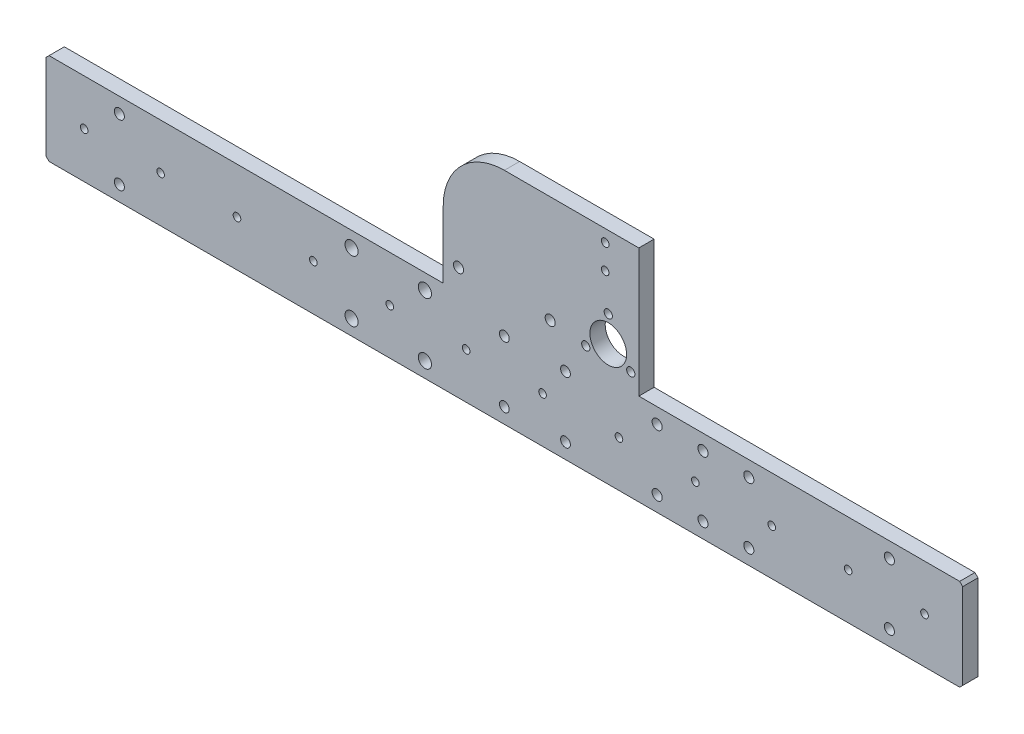
SolidWorks part; units mm, degrees
material "5052-O"
ref_plane "前基準面" through (0, 0, 0) normal (0, 0, 1) x (1, 0, 0)
ref_plane "上基準面" through (0, 0, 0) normal (0, 1, 0) x (1, 0, 0)
ref_plane "右基準面" through (0, 0, 0) normal (1, 0, 0) x (0, 0, -1)
sketch "草圖1" plane through (0, 0, 0) normal (0, 0, 1) x (1, 0, 0)
  line L1 (-150, -15) -> (150, -15)
  line L2 (-150, -15) -> (-150, 15)
  line L3 (-150, 15) -> (150, 15)
  line L4 (150, -15) -> (150, 15)
  line L5 (-150, -15) -> (150, 15) construction
  line L6 (-150, 15) -> (150, -15) construction
  point P0 (0, 0)
  dimension "D1" = 300
  dimension "D2" = 30
extrude "填料-伸長1" add sketch "草圖1" along normal blind 5
chamfer "導角1" distance 1 angle 45 4 edges at (150, -15, 2.5) (150, 15, 2.5) (-150, -15, 2.5) (-150, 15, 2.5)
hole_wizard "M3 餘隙孔1" positions "草圖7" profile "草圖8" hole size "M3" standard "Ansi Metric" end condition through all
sketch "草圖7" plane through (0, 0, 5) normal (0, 0, 1) x (1, 0, 0)
  line L0 (0, 0) -> (10, 0) construction
  line L4 (0, -10) -> (20, -10) construction
  line L5 (0, -10) -> (0, 10) construction
  line L6 (0, 10) -> (20, 10) construction
  line L7 (20, -10) -> (20, 10) construction
  line L8 (0, -10) -> (20, 10) construction
  line L9 (0, 10) -> (20, -10) construction
  point P9 (20, 10)
  point P60 (0, -10)
  point P61 (0, 10)
  point P62 (20, -10)
  dimension "D1" = 10
  dimension "D2" = 20
  dimension "D3" = 20
sketch "草圖8" plane through (20, -10, 5) normal (1, 0, 0) x (0, -1, 0)
  line L0 (0, 0) -> (0, 5)
  line L1 (0, 5) -> (1.6, 5)
  line L2 (1.6, 5) -> (1.6, 0)
  line L5 (1.6, 0) -> (0, 0)
  line L11 (0, -6.35) -> (0, 107.95) construction
  dimension "貫穿孔直徑" = 3.2
  dimension "貫穿孔深度" = 5
hole_wizard "M3x0.5 螺紋孔1" positions "草圖3" profile "草圖4" tap size "M3x0.5" standard "Ansi Metric" end condition through all
sketch "草圖3" plane through (0, 0, 5) normal (0, 0, 1) x (1, 0, 0)
  line L0 (-12.5, 0) -> (12.5, 0) construction
  point P0 (-12.5, 0)
  dimension "D1" = 25
sketch "草圖4" plane through (-12.5, 0, 5) normal (1, 0, 0) x (0, -1, 0)
  line L0 (0, 0) -> (0, 5)
  line L1 (0, 5) -> (1.25, 5)
  line L2 (1.25, 5) -> (1.25, 0)
  line L5 (1.25, 0) -> (0, 0)
  line L11 (0, -6.35) -> (0, 107.95) construction
  dimension "貫穿螺孔鑽直徑" = 2.5
  dimension "貫穿螺孔鑽深度" = 5
hole_wizard "M4x0.7 螺紋孔1" positions "草圖9" profile "草圖10" tap size "M4x0.7" standard "Ansi Metric" end condition through all
sketch "草圖9" plane through (0, 0, 5) normal (0, 0, 1) x (1, 0, 0)
  line L1 (50, -10) -> (80, -10) construction
  line L2 (50, -10) -> (50, 10) construction
  line L3 (50, 10) -> (80, 10) construction
  line L4 (80, -10) -> (80, 10) construction
  line L5 (50, -10) -> (80, 10) construction
  line L6 (50, 10) -> (80, -10) construction
  line L7 (0, 0) -> (65, 0) construction
  point P2 (80, 10)
  point P55 (50, -10)
  point P56 (50, 10)
  point P57 (80, -10)
  point P68 (65, 0)
  point P78 (65, 10)
  point P80 (65, -10)
  dimension "D1" = 30
  dimension "D2" = 20
  dimension "D3" = 65
sketch "草圖10" plane through (80, 10, 5) normal (1, 0, 0) x (0, -1, 0)
  line L0 (0, 0) -> (0, 5)
  line L1 (0, 5) -> (1.65, 5)
  line L2 (1.65, 5) -> (1.65, 0)
  line L5 (1.65, 0) -> (0, 0)
  line L11 (0, -6.35) -> (0, 107.95) construction
  dimension "砮 脸ふ苝 畖" = 3.3
  dimension "砮 脸ふ苝瞏 " = 5
hole_wizard "M4x0.7 螺紋孔2" positions "草圖11" profile "草圖12" tap size "M4x0.7" standard "Ansi Metric" end condition through all
sketch "草圖11" plane through (0, 0, 5) normal (0, 0, 1) x (1, 0, 0)
  line L0 (-150, 0) -> (-126, 0) construction
  line L1 (-150, 14) -> (-150, -14) construction
  line L4 (-126, -10) -> (-126, 10) construction
  point P9 (-126, -10)
  point P10 (-126, 10)
  dimension "D1" = 20
  dimension "D2" = 24
sketch "草圖12" plane through (-126, 10, 5) normal (1, 0, 0) x (0, -1, 0)
  line L0 (0, 0) -> (0, 5)
  line L1 (0, 5) -> (1.65, 5)
  line L2 (1.65, 5) -> (1.65, 0)
  line L5 (1.65, 0) -> (0, 0)
  line L11 (0, -6.35) -> (0, 107.95) construction
  dimension "貫穿螺孔鑽直徑" = 3.3
  dimension "貫穿螺孔鑽深度" = 5
pattern_linear "直線複製排列1" count 6 spacing 25 along (-1, 0, 0) count 7 spacing 25 along (1, 0, 0) of "M3x0.5 螺紋孔1"
mirror "鏡射1" about plane through (0, 0, 0) normal (1, 0, 0) of "M4x0.7 螺紋孔2"
sketch "草圖16" plane through (0, 0, 0) normal (0, 0, 1) x (1, 0, 0)
  line L0 (-20, 15) -> (44, 15)
  line L1 (149, 15) -> (-149, 15) construction
  line L4 (-20, 37) -> (-20, 15)
  line L5 (0, 0) -> (0, 57) construction
  line L9 (44, 15) -> (44, 57)
  line L10 (44, 57) -> (0, 57)
  arc A1 (-20, 37) -> (0, 57) centre (0, 37) cw
  dimension "D3" = 22
  dimension "D1" = 20
  dimension "D2" = 57
  dimension "D4" = 44
extrude "填料-伸長3" add sketch "草圖16" along normal through all
sketch "草圖13" plane through (0, 0, 0) normal (0, 0, 1) x (1, 0, 0)
  circle A1 centre (34, 24.8) radius 6
  dimension "D1" = 11.9701
  dimension "D2" = 12
  dimension "D3" = 24.8
  dimension "D4" = 34
  dimension "D5" = 34
extrude "除料-伸長2" cut sketch "草圖13" along normal through all
hole_wizard "M2.5 餘隙孔1" positions "草圖14" profile "草圖15" hole size "M2.5" standard "Ansi Metric" end condition through all
sketch "草圖14" plane through (0, 0, 5) normal (0, 0, 1) x (1, 0, 0)
  line L2 (34, 24.8) -> (34, 33.3) construction
  circle A0 centre (34, 24.8) radius 6 construction
  point P1 (34, 33.3)
  point P44 (34, 33.3)
  dimension "D1" = 8.5
sketch "草圖15" plane through (34, 33.3, 5) normal (1, 0, 0) x (0, -1, 0)
  line L0 (0, 0) -> (0, 5)
  line L1 (0, 5) -> (1.35, 5)
  line L2 (1.35, 5) -> (1.35, 0)
  line L5 (1.35, 0) -> (0, 0)
  line L11 (0, -6.35) -> (0, 107.95) construction
  dimension "貫穿孔直徑" = 2.7
  dimension "貫穿孔深度" = 5
hole_wizard "M4x0.7 螺紋孔3" positions "草圖19" profile "草圖20" tap size "M4x0.7" standard "Ansi Metric" end condition through all
sketch "草圖19" plane through (0, 0, 5) normal (0, 0, 1) x (1, 0, 0)
  line L0 (0, 57) -> (0, 22) construction
  line L4 (-15, 22) -> (15, 22) construction
  point P9 (-15, 22)
  point P10 (15, 22)
  dimension "D1" = 30
  dimension "D2" = 22
sketch "草圖20" plane through (15, 22, 5) normal (1, 0, 0) x (0, -1, 0)
  line L0 (0, 0) -> (0, 5)
  line L1 (0, 5) -> (1.65, 5)
  line L2 (1.65, 5) -> (1.65, 0)
  line L5 (1.65, 0) -> (0, 0)
  line L11 (0, -6.35) -> (0, 107.95) construction
  dimension "貫穿螺孔鑽直徑" = 3.3
  dimension "貫穿螺孔鑽深度" = 5
hole_wizard "M4 餘隙孔1" positions "草圖21" profile "草圖22" hole size "M4" standard "Ansi Metric" end condition through all
sketch "草圖21" plane through (0, 0, 5) normal (0, 0, 1) x (1, 0, 0)
  line L0 (0, 0) -> (-38, 0) construction
  line L4 (-50, -10) -> (-26, -10) construction
  line L5 (-50, -10) -> (-50, 10) construction
  line L6 (-50, 10) -> (-26, 10) construction
  line L7 (-26, -10) -> (-26, 10) construction
  line L8 (-50, -10) -> (-26, 10) construction
  line L9 (-50, 10) -> (-26, -10) construction
  point P11 (-26, 10)
  point P60 (-50, -10)
  point P61 (-50, 10)
  point P62 (-26, -10)
  dimension "D1" = 38
  dimension "D2" = 24
  dimension "D3" = 20
sketch "草圖22" plane through (-26, -10, 5) normal (1, 0, 0) x (0, -1, 0)
  line L0 (0, 0) -> (0, 5)
  line L1 (0, 5) -> (2.15, 5)
  line L2 (2.15, 5) -> (2.15, 0)
  line L5 (2.15, 0) -> (0, 0)
  line L11 (0, -6.35) -> (0, 107.95) construction
  dimension "貫穿孔直徑" = 4.3
  dimension "貫穿孔深度" = 5
hole_wizard "M3x0.5 螺紋孔2" positions "草圖23" profile "草圖24" tap size "M3x0.5" standard "Ansi Metric" end condition through all
sketch "草圖23" plane through (0, 0, 5) normal (0, 0, 1) x (1, 0, 0)
  line L0 (33, 53) -> (33, 45) construction
  line L3 (44, 15) -> (44, 57) construction
  line L4 (44, 57) -> (0, 57) construction
  point P0 (33, 53)
  point P1 (33, 45)
  dimension "D1" = 11
  dimension "D2" = 8
  dimension "D3" = 4
sketch "草圖24" plane through (33, 53, 5) normal (1, 0, 0) x (0, -1, 0)
  line L0 (0, 0) -> (0, 5)
  line L1 (0, 5) -> (1.25, 5)
  line L2 (1.25, 5) -> (1.25, 0)
  line L5 (1.25, 0) -> (0, 0)
  line L11 (0, -6.35) -> (0, 107.95) construction
  dimension "貫穿螺孔鑽直徑" = 2.5
  dimension "貫穿螺孔鑽深度" = 5
pattern_circular "環狀複製排列1" count 3 over 360 about axis through (34, 24.8, 0) along (0, 0, 1) of "M2.5 餘隙孔1"
